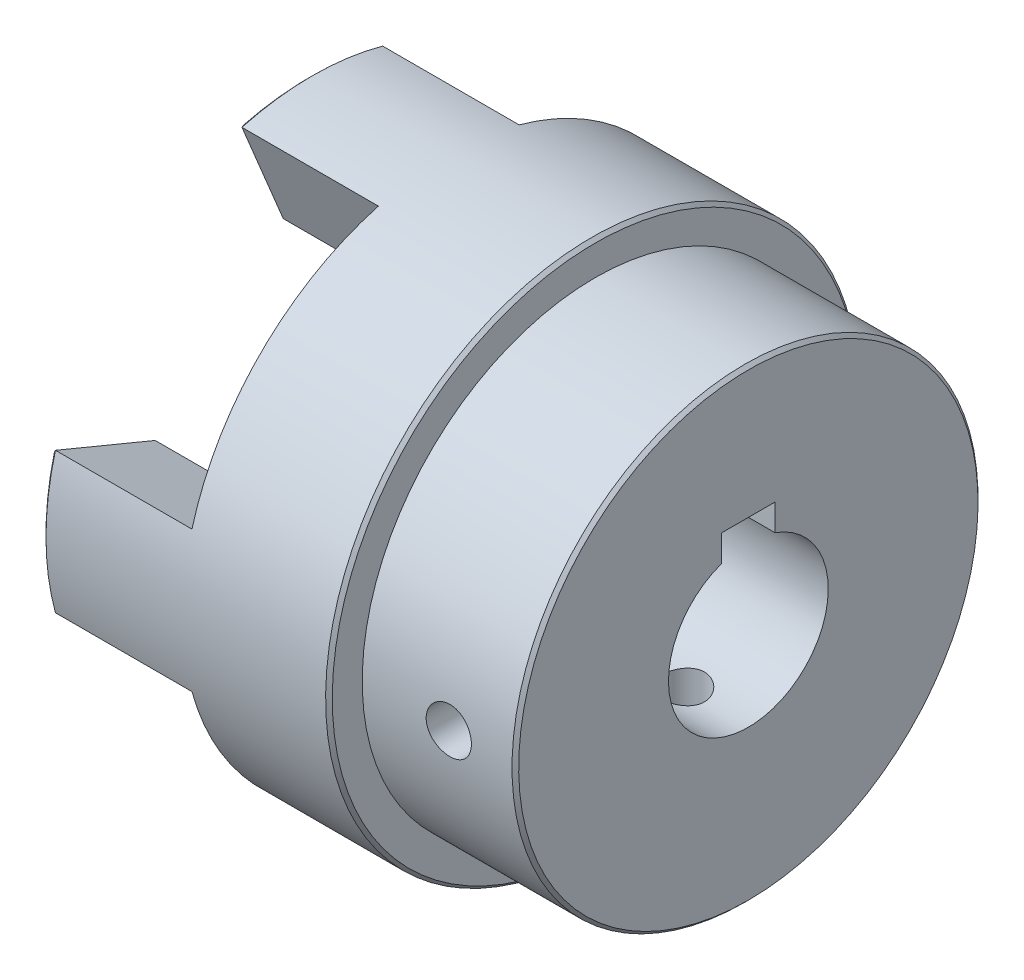
SolidWorks part; units mm, degrees
ref_plane "Front Plane" through (0, 0, 0) normal (0, 0, 1) x (1, 0, 0)
ref_plane "Top Plane" through (0, 0, 0) normal (0, 1, 0) x (1, 0, 0)
ref_plane "Right Plane" through (0, 0, 0) normal (1, 0, 0) x (0, 0, -1)
sketch "Sketch1" plane through (0, 0, 0) normal (0, 0, 1) x (1, 0, 0)
  line L0 (-33, 0) -> (33, 0) construction
  line L1 (-33, 40) -> (10, 40)
  line L2 (10, 40) -> (10, 35)
  line L3 (10, 35) -> (33, 35)
  line L4 (-33, 40) -> (-33, 0)
  line L5 (33, 35) -> (33, 0)
  line L6 (-33, 0) -> (33, 0)
  point P3 (0, 0)
  dimension "D1" = 66
  dimension "D2" = 23
  dimension "D3" = 80
  dimension "D4" = 70
revolve "Revolve1" add sketch "Sketch1" angle 360 about L0
sketch "Sketch2" plane through (-33, 0, 0) normal (-1, 0, 0) x (0, 0, 1)
  line L0 (0, 0) -> (0, 40) construction
  line L1 (-10.5694, 38.5783) -> (-4.365, 23.5997)
  line L2 (38.5783, 10.5694) -> (23.5997, 4.365)
  line L3 (4.365, 23.5997) -> (10.5694, 38.5783)
  line L4 (23.5997, -4.365) -> (38.5783, -10.5694)
  line L5 (10.5694, -38.5783) -> (4.365, -23.5997)
  line L6 (-4.365, -23.5997) -> (-10.5694, -38.5783)
  line L7 (-38.5783, -10.5694) -> (-23.5997, -4.365)
  line L8 (-23.5997, 4.365) -> (-38.5783, 10.5694)
  circle A0 centre (0, 0) radius 40 construction
  arc A1 (-4.365, 23.5997) -> (4.365, 23.5997) centre (0, 0) cw
  arc A2 (10.5694, 38.5783) -> (-10.5694, 38.5783) centre (0, 0) ccw
  arc A3 (38.5783, -10.5694) -> (38.5783, 10.5694) centre (0, 0) ccw
  arc A4 (23.5997, 4.365) -> (23.5997, -4.365) centre (0, 0) cw
  arc A5 (-10.5694, -38.5783) -> (10.5694, -38.5783) centre (0, 0) ccw
  arc A6 (4.365, -23.5997) -> (-4.365, -23.5997) centre (0, 0) cw
  arc A7 (-38.5783, 10.5694) -> (-38.5783, -10.5694) centre (0, 0) ccw
  arc A8 (-23.5997, -4.365) -> (-23.5997, 4.365) centre (0, 0) cw
  point P3 (0, 24)
  point P26 (0, 0)
  dimension "D1" = 24
  dimension "D2" = 8.73
  dimension "D3" = 45
  dimension "D4" = 22.5
  dimension "D5" = 4
extrude "Cut-Extrude1" cut sketch "Sketch2" against normal blind 21 flip side to cut
chamfer "Chamfer1" distance 0.5 angle 45 16 edges at (-33, 0, 24) (-33, 7.4672, 31.089) (-33, 0, 40) (-33, -7.4672, 31.089) (-33, -40, 0) (-33, -31.089, 7.4672) (-33, -24, 0) (-33, -31.089, -7.4672) (-33, 0, -24) (-33, -7.4672, -31.089) (-33, 0, -40) (-33, 7.4672, -31.089) (-33, 31.089, -7.4672) (-33, 24, 0) (-33, 31.089, 7.4672) (-33, 40, 0)
sketch "Sketch3" plane through (-12, 0, 0) normal (-1, 0, 0) x (0, 0, 1)
  line L0 (-4, 11.3137) -> (-4, 15.3)
  line L1 (-4, 15.3) -> (4, 15.3)
  line L2 (4, 15.3) -> (4, 11.3137)
  arc A0 (-4, 11.3137) -> (4, 11.3137) centre (0, 0) ccw
  point P5 (-10.3853, 6.0122)
  point P8 (-5.8052, 10.5024)
  point P9 (-2.5429, 22.1003)
  point P10 (-5.3872, 10.5024)
  point P11 (-5.4769, 19.7373)
  point P12 (5.8052, 19.8949)
  point P13 (0, 15.3)
  point P14 (-4.4163, 15.3)
  dimension "D1" = 24
  dimension "D2" = 15.3
  dimension "D3" = 8
extrude "Cut-Extrude2" cut sketch "Sketch3" against normal up to next
sketch "Sketch7" plane through (0, 0, 0) normal (0, 0, 1) x (1, 0, 0)
  line L0 (0, 0) -> (42.2143, 0) construction
  line L1 (33, -12) -> (33, 11.3137) construction
  point P4 (23, 0)
  dimension "D1" = 10
hole_wizard "M8x1.25 Tapped Hole1" positions "Sketch7" profile "Sketch9" tap size "M8x1.25" standard "ANSI Metric"
sketch "Sketch9" plane through (23, 0, 0) normal (1, 0, 0) x (0, 1, 0)
  line L0 (0, 0) -> (0, 35)
  line L1 (0, 35) -> (3.4, 35)
  line L2 (3.4, 35) -> (3.4, 0)
  line L5 (3.4, 0) -> (0, 0)
  line L11 (0, -6.35) -> (0, 107.95) construction
  dimension "Thru Tap Drill Dia." = 6.8
  dimension "Thru Tap Drill Depth" = 35
cosmetic thread "Hole Thread1" parameters "D2"=8
pattern_circular "CirPattern1" count 2 over 90 about axis through (10, 0, 0) along (-1, 0, 0) of "M8x1.25 Tapped Hole1"
cosmetic thread "Hole Thread2" parameters "D2"=8
chamfer "Chamfer2" distance 0.5 angle 45 2 edges at (33, -35, 0) (10, -40, 0)
